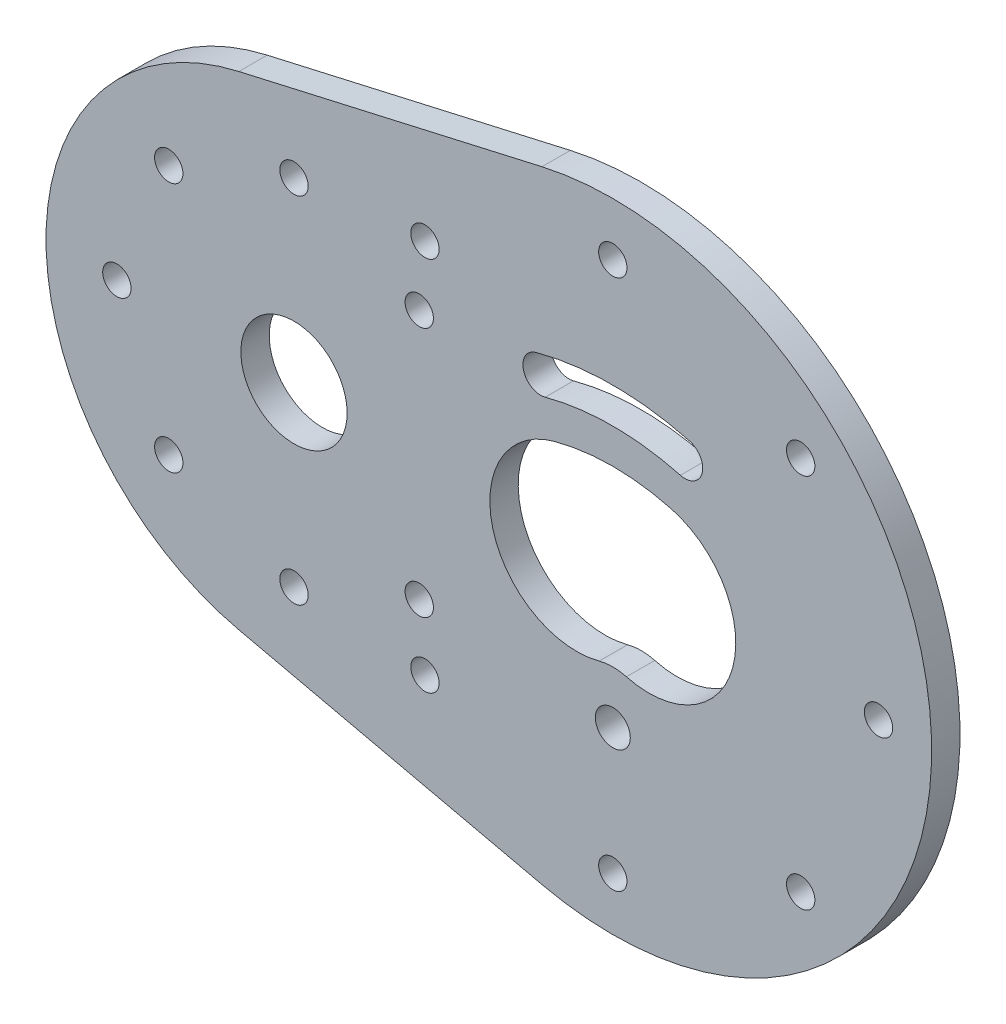
SolidWorks part; units mm, degrees
ref_plane "Front Plane" through (0, 0, 0) normal (0, 0, 1) x (1, 0, 0)
ref_plane "Top Plane" through (0, 0, 0) normal (0, 1, 0) x (1, 0, 0)
ref_plane "Right Plane" through (0, 0, 0) normal (1, 0, 0) x (0, 0, -1)
sketch "Sketch1" plane through (0, 0, 0) normal (0, 0, 1) x (1, 0, 0)
  line L0 (0, 0) -> (0, 36.4546) construction
  line L1 (0, 0) -> (-10.2847, 38.3829) construction
  line L2 (-28.575, 12.5) -> (0, 12.5) construction
  line L4 (-91.5313, 56.95) -> (35.4687, 56.95)
  line L5 (-91.5313, 56.95) -> (-91.5313, -31.95)
  line L6 (-91.5313, -31.95) -> (35.4687, -31.95)
  line L7 (35.4687, 56.95) -> (35.4687, -31.95)
  line L8 (-91.5313, 56.95) -> (35.4687, -31.95) construction
  line L9 (-91.5313, -31.95) -> (35.4687, 56.95) construction
  arc A0 (5.2502, 19.5939) -> (1.2203, 4.5542) centre (3.2352, 12.0741) cw
  arc A1 (5.2502, 19.5939) -> (-5.2502, 19.5939) centre (0, 0) ccw
  circle A2 centre (0, 12.5) radius 12.5 construction
  circle A3 centre (0, 0) radius 1.5649
  arc A4 (10.8253, 6.25) -> (-10.8253, 6.25) centre (0, 0) ccw construction
  arc A5 (1.2203, 4.5542) -> (-1.2203, 4.5542) centre (0, 0) ccw
  arc A6 (-5.2502, 19.5939) -> (-1.2203, 4.5542) centre (-3.2352, 12.0741) ccw
  circle A7 centre (0, 25) radius 1.5875 construction
  arc A8 (6.8814, 25.6816) -> (-6.8814, 25.6816) centre (0, 0) ccw
  arc A9 (6.0596, 22.6147) -> (-6.0596, 22.6147) centre (0, 0) ccw
  circle A10 centre (0, 0) radius 25 construction
  arc A11 (-6.8814, 25.6816) -> (-6.0596, 22.6147) centre (-6.4705, 24.1481) ccw
  arc A12 (6.8814, 25.6816) -> (6.0596, 22.6147) centre (6.4705, 24.1481) cw
  circle A13 centre (-28.575, 12.5) radius 4.7625
  circle A14 centre (-28.575, 12.5) radius 25.4 construction
  point P0 (0, 0)
  point P18 (-28.0313, 12.5)
  dimension "D4" = 25
  dimension "D6" = 50.8
  dimension "D2" = 3.175
  dimension "D3" = 9.525
  dimension "D9" = 7.7851
  dimension "D1" = 15
  dimension "D5" = 28.575
  dimension "D7" = 88.9
  dimension "D8" = 127
extrude "Boss-Extrude1" add sketch "Sketch1" along normal blind 2.54
sketch "Sketch2" plane through (0, 0, 2.54) normal (0, 0, 1) x (1, 0, 0)
  line L0 (-28.575, 12.5) -> (43.934, 12.5) construction
  line L1 (0, 0) -> (0, 70.9306) construction
  line L2 (-33.5139, 34.1693) -> (-6.35, 40.3605)
  line L3 (-33.5139, -9.1693) -> (-6.35, -15.3605)
  line L5 (-107.0175, 80.3674) -> (70.5021, 80.3674)
  line L6 (-107.0175, 80.3674) -> (-107.0175, -46.3508)
  line L7 (-107.0175, -46.3508) -> (70.5021, -46.3508)
  line L8 (70.5021, 80.3674) -> (70.5021, -46.3508)
  arc A0 (-6.35, -15.3605) -> (-6.35, 40.3605) centre (0, 12.5) ccw
  arc A1 (-33.5139, 34.1693) -> (-33.5139, -9.1693) centre (-28.575, 12.5) ccw
  dimension "D1" = 57.15
  dimension "D2" = 44.45
extrude "Cut-Extrude1" cut sketch "Sketch2" against normal through all
sketch "Sketch4" plane through (0, 0, 2.54) normal (0, 0, 1) x (1, 0, 0)
  line L0 (-28.575, 12.5) -> (35.849, 12.5) construction
  line L1 (0, 0) -> (0, 48.1146) construction
  circle A0 centre (-28.575, 12.5) radius 15.875 construction
  circle A1 centre (0, 12.5) radius 23.8125 construction
  circle A2 centre (-28.575, 28.375) radius 1.27
  circle A3 centre (0, 36.3125) radius 1.27
  circle A4 centre (-17.3497, 23.7253) radius 1.27
  circle A5 centre (-12.7, 12.5) radius 1.27 [skipped]
  circle A6 centre (-17.3497, 1.2747) radius 1.27
  circle A7 centre (-28.575, -3.375) radius 1.27
  circle A8 centre (-39.8003, 1.2747) radius 1.27
  circle A9 centre (-44.45, 12.5) radius 1.27
  circle A10 centre (-39.8003, 23.7253) radius 1.27
  circle A11 centre (16.838, 29.338) radius 1.27
  circle A12 centre (23.8125, 12.5) radius 1.27
  circle A13 centre (16.838, -4.338) radius 1.27
  circle A14 centre (0, -11.3125) radius 1.27
  circle A15 centre (-16.838, -4.338) radius 1.27
  circle A16 centre (-23.8125, 12.5) radius 1.27 [skipped]
  circle A17 centre (-16.838, 29.338) radius 1.27
  dimension "D1" = 47.625
  dimension "D2" = 31.75
  dimension "D3" = 2.54
  dimension "D4" = 2.54
  dimension "D5" = 8
  dimension "D6" = 8
extrude "Cut-Extrude2" cut sketch "Sketch4" against normal through all
